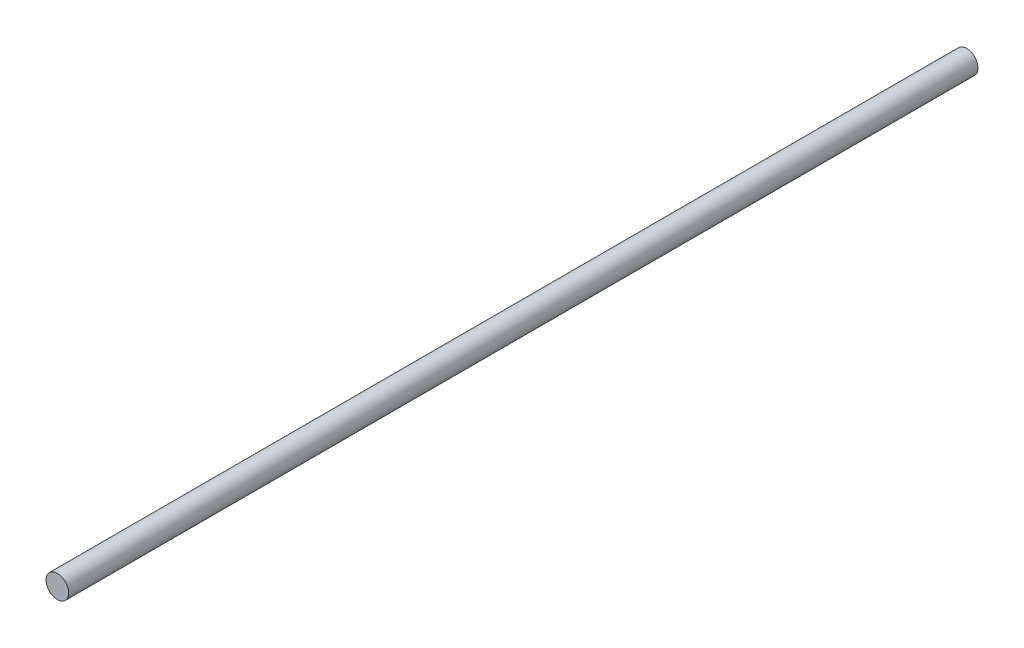
SolidWorks part; units mm, degrees
ref_plane "Front Plane" through (0, 0, 0) normal (0, 0, 1) x (1, 0, 0)
ref_plane "Top Plane" through (0, 0, 0) normal (0, 1, 0) x (1, 0, 0)
ref_plane "Right Plane" through (0, 0, 0) normal (1, 0, 0) x (0, 0, -1)
sketch "Sketch1" plane through (0, 0, 0) normal (0, 0, 1) x (1, 0, 0)
  circle A0 centre (0, 0) radius 2
  dimension "D1" = 4
extrude "Boss-Extrude1" add sketch "Sketch1" along normal blind 160
